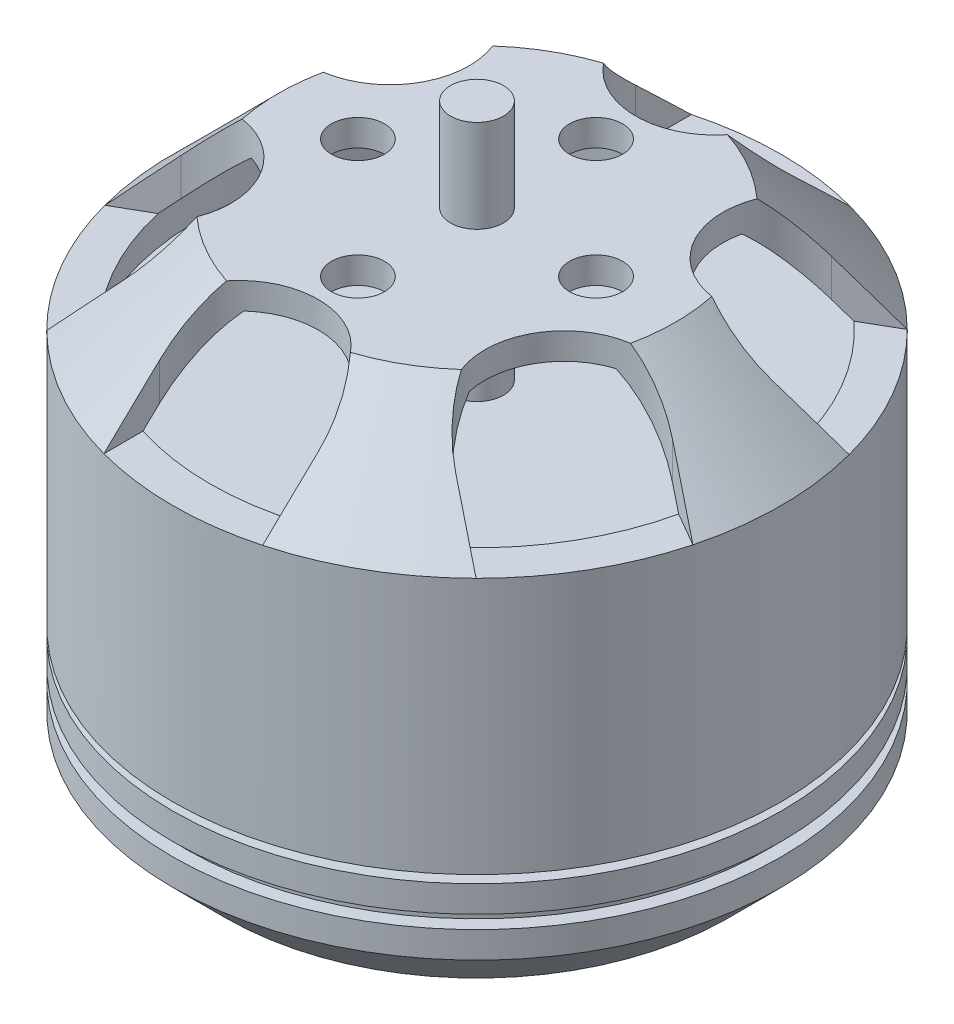
SolidWorks part; units mm, degrees
ref_plane "Front Plane" through (0, 0, 0) normal (0, 0, 1) x (1, 0, 0)
ref_plane "Top Plane" through (0, 0, 0) normal (0, 1, 0) x (1, 0, 0)
ref_plane "Right Plane" through (0, 0, 0) normal (1, 0, 0) x (0, 0, -1)
sketch "Sketch1" plane through (0, 0, 0) normal (0, 0, 1) x (1, 0, 0)
  line L0 (0, 18.4706) -> (0, 0)
  line L1 (1, -3.5294) -> (9.5, -3.5294)
  line L2 (9.5, -3.5294) -> (11.5, -1.5294)
  line L3 (11.5, -1.5294) -> (11.5, -0.5294)
  line L4 (11.5, 10.9706) -> (7.5, 14.9706)
  line L5 (7.5, 14.9706) -> (1, 14.9706)
  line L6 (1, 14.9706) -> (1, 18.4706)
  line L7 (1, 18.4706) -> (0, 18.4706)
  line L8 (0, 0) -> (0, -5.3294)
  line L9 (0, -5.3294) -> (1, -5.3294)
  line L10 (1, -5.3294) -> (1, -3.5294)
  line L11 (2, 13.9706) -> (7.0858, 13.9706)
  line L12 (7.0858, 13.9706) -> (10.5, 10.5563)
  line L13 (10.5, 10.5563) -> (10.5, 9.3319)
  line L14 (10.5, 9.3319) -> (1, 9.3319)
  line L15 (1, 9.3319) -> (1, 12.9706)
  line L16 (1, 12.9706) -> (2, 12.9706)
  line L17 (2, 12.9706) -> (2, 13.9706)
  line L18 (11.5, -0.5294) -> (11, -0.5294)
  line L19 (11, -0.5294) -> (11, -0.0294)
  line L20 (11, -0.0294) -> (11.5, -0.0294)
  line L21 (11.5, 0.9706) -> (9.5, 0.9706)
  line L22 (9.5, 0.9706) -> (9.5, 1.2706)
  line L23 (9.5, 1.2706) -> (11.5, 1.2706)
  line L24 (11.5, 1.2706) -> (11.5, 10.9706)
  line L25 (11.5, -0.0294) -> (11.5, 0.9706)
  dimension "D1" = 23.8
  dimension "D2" = 1.8
  dimension "D3" = 45
  dimension "D4" = 2
  dimension "D5" = 1
  dimension "D6" = 1
  dimension "D7" = 45
  dimension "D8" = 3.5
  dimension "D9" = 11.5
  dimension "D10" = 1
  dimension "D11" = 1
  dimension "D12" = 1
  dimension "D13" = 1
  dimension "D14" = 1
  dimension "D15" = 1
  dimension "D16" = 4
  dimension "D17" = 0.5
  dimension "D18" = 0.5
  dimension "D19" = 1
  dimension "D20" = 2
  dimension "D21" = 0.3
  dimension "D22" = 1
revolve "Revolve1" add sketch "Sketch1" angle 360 about L0
sketch "Sketch2" plane through (0, 14.9706, 0) normal (0, 1, 0) x (1, 0, 0)
  line L0 (0, 0) -> (0, 9) construction
  line L1 (-3, 9) -> (-3, 15.3814)
  line L2 (-3, 15.3814) -> (3, 15.3814)
  line L3 (3, 15.3814) -> (3, 9)
  line L4 (14.8207, 5.0926) -> (9.2942, 1.9019)
  line L5 (11.8207, 10.2888) -> (14.8207, 5.0926)
  line L6 (6.2942, 7.0981) -> (11.8207, 10.2888)
  line L7 (11.8207, -10.2888) -> (6.2942, -7.0981)
  line L8 (14.8207, -5.0926) -> (11.8207, -10.2888)
  line L9 (9.2942, -1.9019) -> (14.8207, -5.0926)
  line L10 (-3, -15.3814) -> (-3, -9)
  line L11 (3, -15.3814) -> (-3, -15.3814)
  line L12 (3, -9) -> (3, -15.3814)
  line L13 (-14.8207, -5.0926) -> (-9.2942, -1.9019)
  line L14 (-11.8207, -10.2888) -> (-14.8207, -5.0926)
  line L15 (-6.2942, -7.0981) -> (-11.8207, -10.2888)
  line L16 (-11.8207, 10.2888) -> (-6.2942, 7.0981)
  line L17 (-14.8207, 5.0926) -> (-11.8207, 10.2888)
  line L18 (-9.2942, 1.9019) -> (-14.8207, 5.0926)
  circle A0 centre (0, 0) radius 4.5 construction
  circle A1 centre (0, 0) radius 8.3471 construction
  circle A2 centre (0, -4.5) radius 1
  circle A3 centre (-4.5, 0) radius 1
  circle A4 centre (0, 4.5) radius 1
  circle A5 centre (4.5, 0) radius 1
  arc A6 (-3, 9) -> (3, 9) centre (0, 9) ccw
  arc A7 (6.2942, 7.0981) -> (9.2942, 1.9019) centre (7.7942, 4.5) ccw
  arc A8 (9.2942, -1.9019) -> (6.2942, -7.0981) centre (7.7942, -4.5) ccw
  arc A9 (3, -9) -> (-3, -9) centre (0, -9) ccw
  arc A10 (-6.2942, -7.0981) -> (-9.2942, -1.9019) centre (-7.7942, -4.5) ccw
  arc A11 (-9.2942, 1.9019) -> (-6.2942, 7.0981) centre (-7.7942, 4.5) ccw
  point P16 (0, 0)
  point P46 (0, 0)
  dimension "D1" = 9
  dimension "D3" = 2
  dimension "D5" = 6
  dimension "D2" = 9
  dimension "D4" = 4
  dimension "D6" = 6
extrude "Cut-Extrude1" cut sketch "Sketch2" against normal blind 4
sketch "Sketch3" plane through (0, -3.5294, 0) normal (0, -1, 0) x (1, 0, 0)
  circle A0 centre (0, 0) radius 6 construction
  circle A1 centre (0, 0) radius 8 construction
  circle A2 centre (0, 6) radius 1
  circle A3 centre (0, -6) radius 1
  circle A4 centre (-8, 0) radius 1
  circle A5 centre (8, 0) radius 1
  dimension "D1" = 12
  dimension "D2" = 16
  dimension "D3" = 2
extrude "Cut-Extrude2" cut sketch "Sketch3" against normal blind 3
